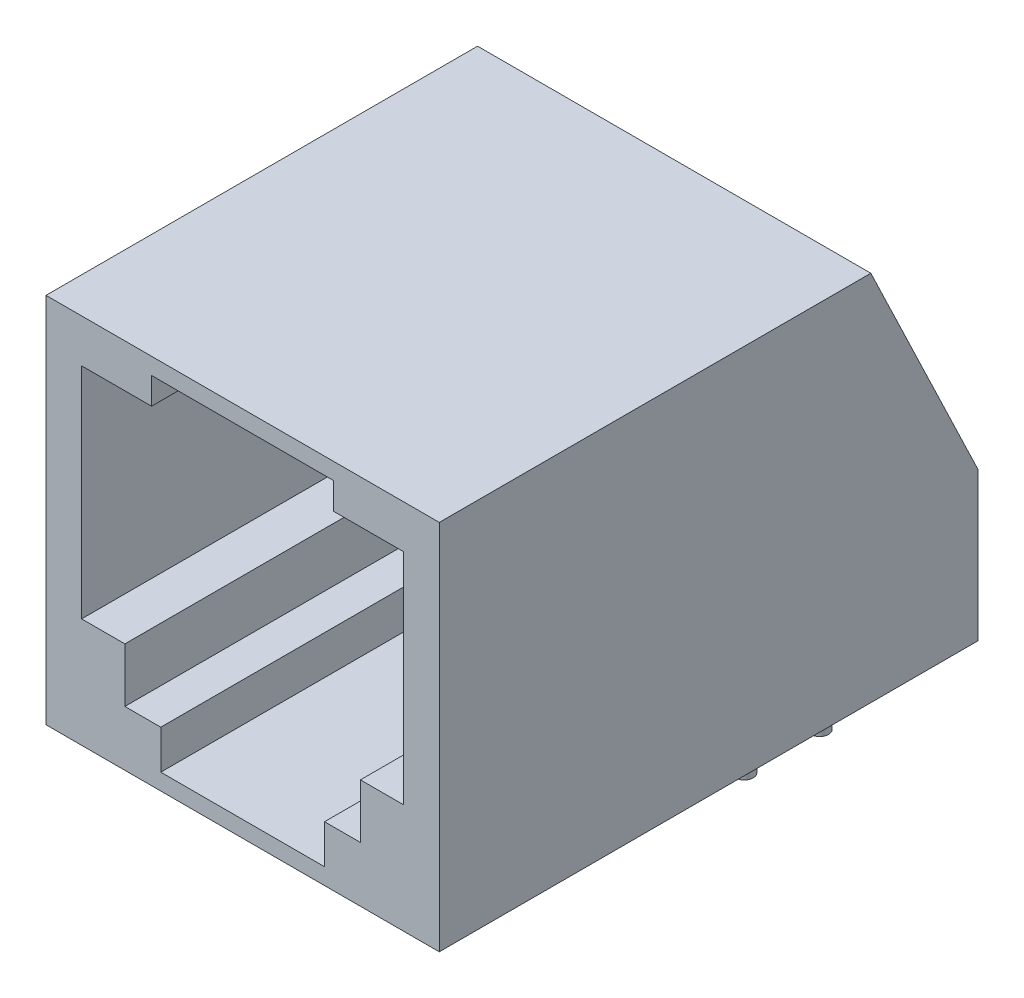
SolidWorks part; units mm, degrees
ref_plane "Front Plane" through (0, 0, 0) normal (0, 0, 1) x (1, 0, 0)
ref_plane "Top Plane" through (0, 0, 0) normal (0, 1, 0) x (1, 0, 0)
ref_plane "Right Plane" through (0, 0, 0) normal (1, 0, 0) x (0, 0, -1)
sketch "Sketch1" plane through (0, 0, 0) normal (1, 0, 0) x (0, 0, -1)
  line L0 (0, 0) -> (0, 12.53)
  line L1 (0, 12.53) -> (14.54, 12.53)
  line L2 (14.54, 12.53) -> (18.15, 5)
  line L3 (18.15, 5) -> (18.15, 0)
  line L4 (18.15, 0) -> (0, 0)
  dimension "D1" = 18.15
  dimension "D2" = 12.53
  dimension "D3" = 5
  dimension "D4" = 14.54
extrude "Boss-Extrude1" add sketch "Sketch1" along normal mid plane 13.25 contours L1 L2 L3 L4 L0
sketch "Sketch2" plane through (0, 0, 0) normal (0, 0, 1) x (1, 0, 0)
  line L0 (-2.7584, 1.8633) -> (-2.7584, 0.55)
  line L1 (-3.9677, 1.8633) -> (-2.7584, 1.8633)
  line L2 (-3.0693, 11.97) -> (3.0693, 11.97)
  line L3 (3.0693, 11.97) -> (3.0693, 11.0732)
  line L4 (3.0693, 11.0732) -> (5.425, 11.0732)
  line L5 (5.425, 11.0732) -> (5.425, 3.6892)
  line L6 (5.425, 3.6892) -> (3.9677, 3.6892)
  line L7 (3.9677, 3.6892) -> (3.9677, 1.8633)
  line L8 (3.9677, 1.8633) -> (2.7584, 1.8633)
  line L9 (2.7584, 1.8633) -> (2.7584, 0.55)
  line L10 (2.7584, 0.55) -> (-2.7584, 0.55)
  line L11 (0, 0) -> (0, 14.1337) construction
  line L12 (-3.9677, 3.6892) -> (-3.9677, 1.8633)
  line L13 (-5.425, 3.6892) -> (-3.9677, 3.6892)
  line L14 (-5.425, 11.0732) -> (-5.425, 3.6892)
  line L15 (-3.0693, 11.0732) -> (-5.425, 11.0732)
  line L16 (-3.0693, 11.97) -> (-3.0693, 11.0732)
  line L17 (6.625, 12.53) -> (-6.625, 12.53) construction
  line L18 (6.625, 0) -> (6.625, 12.53) construction
  line L19 (6.625, 0) -> (-6.625, 0) construction
  point P15 (0, 0.55)
  point P22 (0, 11.97)
  dimension "D1" = 0.56
  dimension "D2" = 1.2
  dimension "D3" = 0.55
extrude "Cut-Extrude1" cut sketch "Sketch2" against normal blind 13.25 contours L15 L14 L13 L12 L1 L0 L10 L9 L8 L7 L6 L5 L4 L3 L2 L16
sketch "Sketch3" plane through (0, 0, 0) normal (0, -1, 0) x (1, 0, 0)
  line L0 (6.625, -18.15) -> (-6.625, -18.15) construction
  line L1 (2.54, -16.9) -> (6.625, -16.9) construction
  line L2 (6.625, -18.15) -> (6.625, 0) construction
  line L3 (-2.54, -16.9) -> (-6.625, -16.9) construction
  line L4 (-6.625, -18.15) -> (-6.625, 0) construction
  line L5 (-2.54, -16.9) -> (-2.54, -14.36) construction
  circle A0 centre (2.54, -16.9) radius 0.3
  circle A1 centre (0, -16.9) radius 0.3
  circle A2 centre (-2.54, -16.9) radius 0.3
  circle A3 centre (0, -14.36) radius 0.3
  circle A4 centre (-2.54, -14.36) radius 0.3
  circle A5 centre (2.54, -14.36) radius 0.3
  dimension "D4" = 0.6
  dimension "D3" = 1.25
  dimension "D5" = 2.54
  dimension "D6" = 2.54
  dimension "D1" = 3
  dimension "D2" = 2
extrude "Boss-Extrude2" add sketch "Sketch3" along normal blind 4 contours A0
